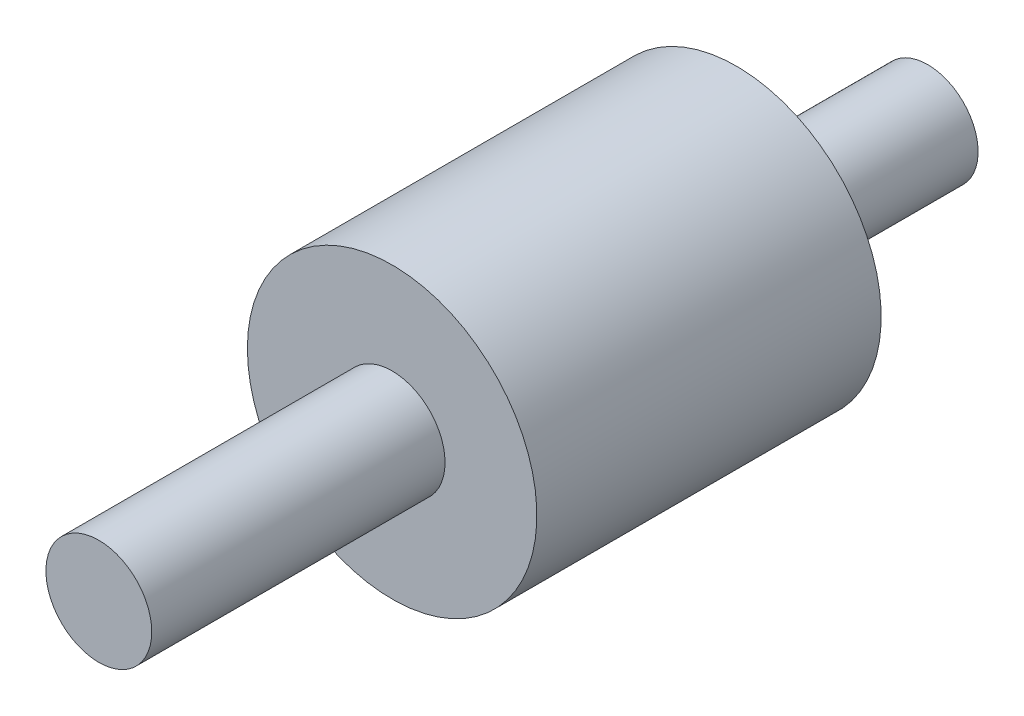
SolidWorks part; units mm, degrees
ref_plane "Front Plane" through (0, 0, 0) normal (0, 0, 1) x (1, 0, 0)
ref_plane "Top Plane" through (0, 0, 0) normal (0, 1, 0) x (1, 0, 0)
ref_plane "Right Plane" through (0, 0, 0) normal (1, 0, 0) x (0, 0, -1)
sketch "Sketch1" plane through (0, 0, 0) normal (0, 0, 1) x (1, 0, 0)
  circle A0 centre (0, 0) radius 4.15
  dimension "D1" = 8.3
extrude "Boss-Extrude1" add sketch "Sketch1" along normal blind 23
sketch "Sketch2" plane through (0, 0, 0) normal (0, 0, -1) x (-1, 0, 0)
  circle A0 centre (0, 0) radius 11.35
  dimension "D1" = 22.7
extrude "Boss-Extrude2" add sketch "Sketch2" along normal blind 27
sketch "Sketch3" plane through (0, 0, -27) normal (0, 0, -1) x (-1, 0, 0)
  circle A0 centre (0, 0) radius 3.95
  dimension "D1" = 7.9
extrude "Boss-Extrude3" add sketch "Sketch3" along normal blind 15
